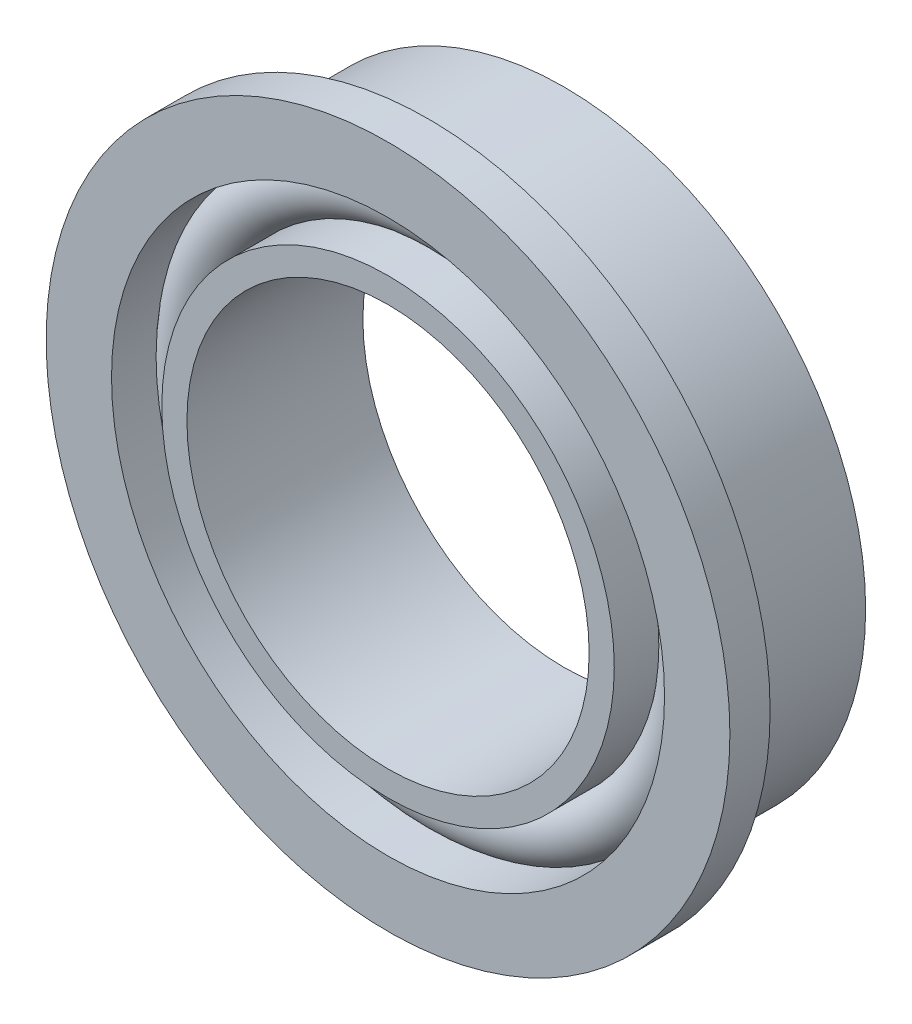
SolidWorks part; units mm, degrees
ref_plane "Front Plane" through (0, 0, 0) normal (0, 0, 1) x (1, 0, 0)
ref_plane "Top Plane" through (0, 0, 0) normal (0, 1, 0) x (1, 0, 0)
ref_plane "Right Plane" through (0, 0, 0) normal (1, 0, 0) x (0, 0, -1)
sketch "Sketch1" plane through (0, 0, 0) normal (0, 0, 1) x (1, 0, 0)
  circle A0 centre (0, 0) radius 4
  circle A1 centre (0, 0) radius 6
  dimension "D1" = 8
  dimension "D2" = 12
extrude "Boss-Extrude1" add sketch "Sketch1" along normal blind 3.5
sketch "Sketch4" plane through (0, 0, 3.5) normal (0, 0, 1) x (1, 0, 0)
  circle A0 centre (0, 0) radius 4.5
  circle A1 centre (0, 0) radius 5.5
  dimension "D1" = 9
  dimension "D2" = 11
extrude "Cut-Extrude1" cut sketch "Sketch4" against normal blind 41.1
sketch "Sketch6" plane through (0, 0, 0) normal (0, 1, 0) x (1, 0, 0)
  line L0 (-5, -2.2653) -> (0, -2.2653) construction
  line L1 (0, -2.2653) -> (0, 0) construction
  circle A0 centre (-5, -2.2653) radius 0.6
  dimension "D1" = 1.2
  dimension "D2" = 5
ref_axis "Axis1" through (0, 0, 3.5) along (0, 0, -1)
revolve "Revolve1" add sketch "Sketch6" angle 360 about axis through (0, 0, 3.5) along (0, 0, -1)
sketch "Sketch8" plane through (0, 0, 3.5) normal (0, 0, 1) x (1, 0, 0)
  circle A0 centre (0, 0) radius 6.8
  circle A1 centre (0, 0) radius 6
  circle A2 centre (0, 0) radius 6
  dimension "D2" = 13.6
  dimension "D1" = 0
extrude "Boss-Extrude3" add sketch "Sketch8" against normal blind 0.8
